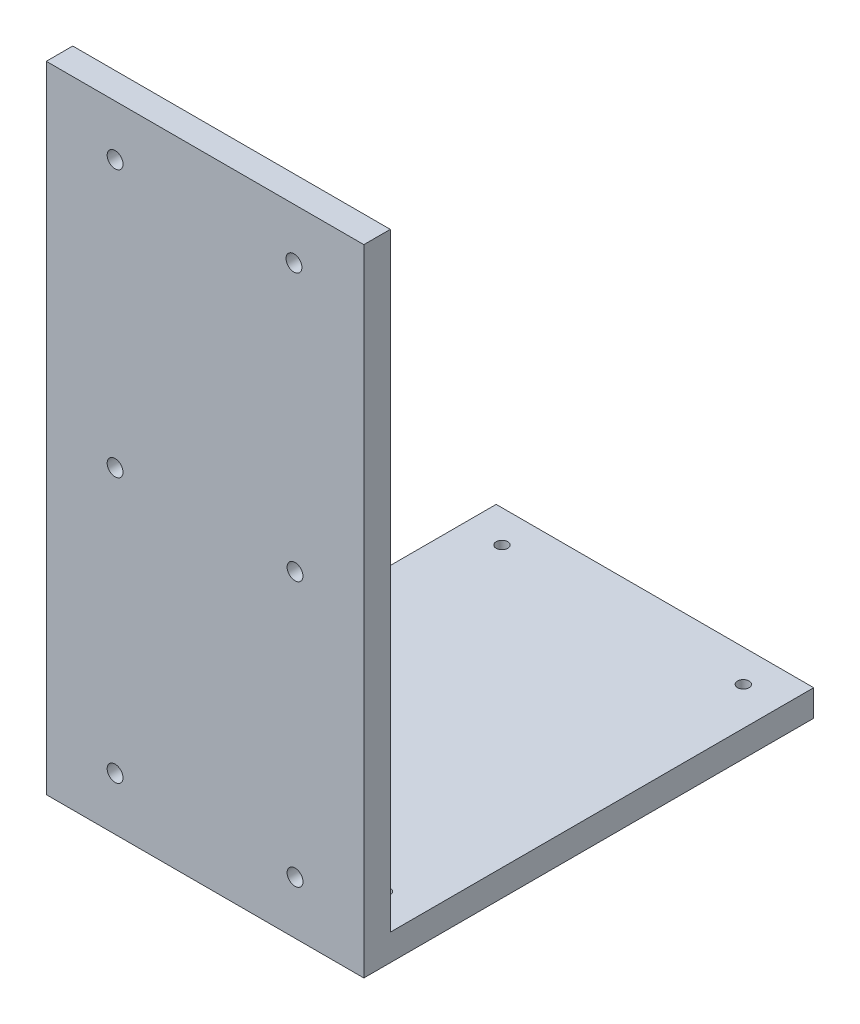
SolidWorks part; units mm, degrees
ref_plane "Front Plane" through (0, 0, 0) normal (0, 0, 1) x (1, 0, 0)
ref_plane "Top Plane" through (0, 0, 0) normal (0, 1, 0) x (1, 0, 0)
ref_plane "Right Plane" through (0, 0, 0) normal (1, 0, 0) x (0, 0, -1)
sketch "Sketch1" plane through (0, 0, 0) normal (0, 0, 1) x (1, 0, 0)
  line L1 (-38.1, 152.4) -> (38.1, 152.4)
  line L2 (-38.1, 152.4) -> (-38.1, 0)
  line L3 (-38.1, 0) -> (38.1, 0)
  line L4 (38.1, 152.4) -> (38.1, 0)
  dimension "D1" = 76.2
  dimension "D2" = 152.4
extrude "Boss-Extrude1" add sketch "Sketch1" along normal blind 6.35
sketch "Sketch3" plane through (0, 0, 0) normal (0, 0, 1) x (1, 0, 0)
  line L0 (-38.1, 0) -> (-38.1, 6.35)
  line L1 (-38.1, 152.4) -> (-38.1, 0) construction
  line L2 (-38.1, 6.35) -> (38.1, 6.35)
  line L3 (38.1, 0) -> (38.1, 152.4) construction
  line L4 (38.1, 6.35) -> (38.1, 0)
  line L5 (38.1, 0) -> (-38.1, 0)
  dimension "D1" = 6.35
extrude "Boss-Extrude2" add sketch "Sketch3" against normal blind 101.6
sketch "Sketch4" plane through (0, 0, 6.35) normal (0, 0, 1) x (1, 0, 0)
  line L0 (0, 152.4) -> (0, 0)
  line L1 (38.1, 152.4) -> (-38.1, 152.4) construction
  line L2 (0, 140.208) -> (21.336, 140.208)
  line L3 (0, 140.208) -> (-21.59, 140.208)
  line L4 (0, 76.2) -> (-21.59, 76.2)
  line L5 (0, 76.2) -> (21.59, 76.2)
  line L6 (0, 12.7) -> (21.59, 12.7)
  line L7 (0, 12.7) -> (-21.59, 12.7)
  circle A0 centre (21.336, 140.208) radius 1.905
  circle A1 centre (-21.59, 140.208) radius 1.905
  circle A2 centre (-21.59, 76.2) radius 1.905
  circle A3 centre (21.59, 76.2) radius 1.905
  circle A4 centre (21.59, 12.7) radius 1.905
  circle A5 centre (-21.59, 12.7) radius 1.905
  dimension "D9" = 3.81
  dimension "D10" = 3.81
  dimension "D11" = 3.81
  dimension "D12" = 3.81
  dimension "D13" = 3.81
  dimension "D14" = 3.81
  dimension "D1" = 21.59
  dimension "D2" = 21.59
  dimension "D3" = 21.336
  dimension "D4" = 21.59
  dimension "D5" = 21.59
  dimension "D6" = 21.59
  dimension "D7" = 63.5
  dimension "D8" = 64.008
extrude "Cut-Extrude1" cut sketch "Sketch4" against normal through all
sketch "Sketch5" plane through (0, 6.35, 0) normal (0, 1, 0) x (1, 0, 0)
  line L0 (0, 101.6) -> (0, 0)
  line L1 (38.1, 101.6) -> (-38.1, 101.6) construction
  line L2 (0, 50.8) -> (-28.956, 50.8)
  line L3 (-28.956, 7.747) -> (28.956, 7.747)
  line L4 (-28.956, 7.747) -> (-28.956, 93.853)
  line L5 (-28.956, 93.853) -> (28.956, 93.853)
  line L6 (28.956, 7.747) -> (28.956, 93.853)
  line L7 (-28.956, 7.747) -> (28.956, 93.853) construction
  line L8 (-28.956, 93.853) -> (28.956, 7.747) construction
  circle A0 centre (-28.956, 93.853) radius 1.397
  circle A1 centre (28.956, 93.853) radius 1.397
  circle A2 centre (28.956, 7.747) radius 1.397
  circle A3 centre (-28.956, 7.747) radius 1.397
  point P5 (0, 50.8)
  dimension "D3" = 2.794
  dimension "D1" = 57.912
  dimension "D2" = 86.106
extrude "Cut-Extrude2" cut sketch "Sketch5" against normal through all contours L4 A0 L5 | L5 A0 L4 | A1 L6 L5 | A1 L5 L6 | A3 | A2
